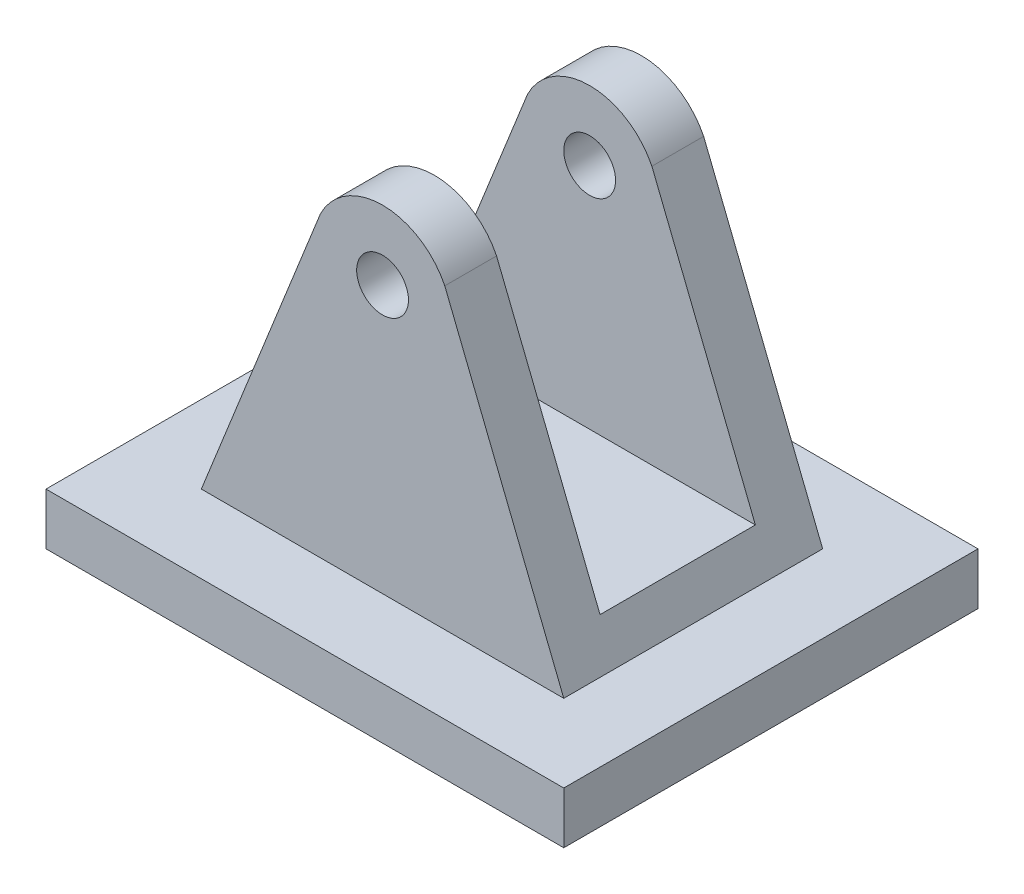
SolidWorks part; units mm, degrees
ref_plane "Front Plane" through (0, 0, 0) normal (0, 0, 1) x (1, 0, 0)
ref_plane "Top Plane" through (0, 0, 0) normal (0, 1, 0) x (1, 0, 0)
ref_plane "Right Plane" through (0, 0, 0) normal (1, 0, 0) x (0, 0, -1)
sketch "Sketch1" plane through (0, 0, 0) normal (0, 1, 0) x (1, 0, 0)
  line L0 (-69.281, 36.9281) -> (30.719, 36.9281)
  line L1 (-69.281, 36.9281) -> (-69.281, -43.0719)
  line L2 (30.719, 36.9281) -> (30.719, -43.0719)
  line L3 (-69.281, -43.0719) -> (30.719, -43.0719)
  line L4 (-69.281, 36.9281) -> (30.719, -43.0719) construction
  line L5 (30.719, 36.9281) -> (-69.281, -43.0719) construction
  point P1 (-19.281, -3.0719)
  dimension "D1" = 100
  dimension "D2" = 80
extrude "Boss-Extrude1" add sketch "Sketch1" along normal blind 10
sketch "Sketch2" plane through (0, 10, 0) normal (0, 1, 0) x (1, 0, 0)
  line L2 (-54.281, -28.0719) -> (15.719, -28.0719)
  line L3 (-54.281, -28.0719) -> (-54.281, 21.9281)
  line L4 (15.719, -28.0719) -> (15.719, 21.9281)
  line L5 (-54.281, 21.9281) -> (15.719, 21.9281)
  line L6 (-54.281, -28.0719) -> (15.719, 21.9281) construction
  line L7 (15.719, -28.0719) -> (-54.281, 21.9281) construction
  point P9 (-19.281, -3.0719)
  dimension "D1" = 70
  dimension "D2" = 50
extrude "Boss-Extrude2" add sketch "Sketch2" along normal blind 65
sketch "Sketch3" plane through (0, 0, 28.0719) normal (0, 0, 1) x (1, 0, 0)
  line L0 (-54.281, 10) -> (-28.3003, 75)
  line L1 (-54.281, 75) -> (15.719, 75) construction
  line L2 (15.719, 10) -> (-10.2618, 75)
  arc A0 (-31.2976, 67.5012) -> (-7.2645, 67.5012) centre (-19.281, 61.6226) cw
  circle A1 centre (-19.281, 61.6226) radius 5
  line M4 (15.719, 10) -> (15.719, 75)
  line M5 (15.719, 75) -> (-54.281, 75)
  line M6 (-54.281, 75) -> (-54.281, 10)
sketch "Sketch5" plane through (15.719, 0, 0) normal (1, 0, 0) x (0, 0, -1)
  line L2 (-28.0719, 75) -> (21.9281, 75) construction
  line L3 (11.9281, 17.5) -> (-18.0719, 17.5)
  line L4 (11.9281, 17.5) -> (11.9281, 67.5)
  line L6 (-18.0719, 17.5) -> (-18.0719, 67.5)
  line L7 (11.9281, 17.5) -> (-18.0719, 67.5) construction
  line L8 (11.9281, 67.5) -> (-18.0719, 17.5) construction
  line L10 (-18.0719, 67.5) -> (-18.0719, 75)
  line L11 (-18.0719, 75) -> (11.9281, 75)
  line L12 (11.9281, 67.5) -> (11.9281, 75)
  point P8 (-3.0719, 42.5)
extrude "Cut-Extrude2" cut sketch "Sketch5" against normal blind 94
sketch "Sketch7" plane through (0, 0, 28.0719) normal (0, 0, 1) x (1, 0, 0)
extrude "Cut-Extrude4" cut sketch "Sketch3" against normal blind 94 contours L0 M6 M5 | L0 A0 M5 | A0 L2 M5 | L2 M4 M5 | A1
